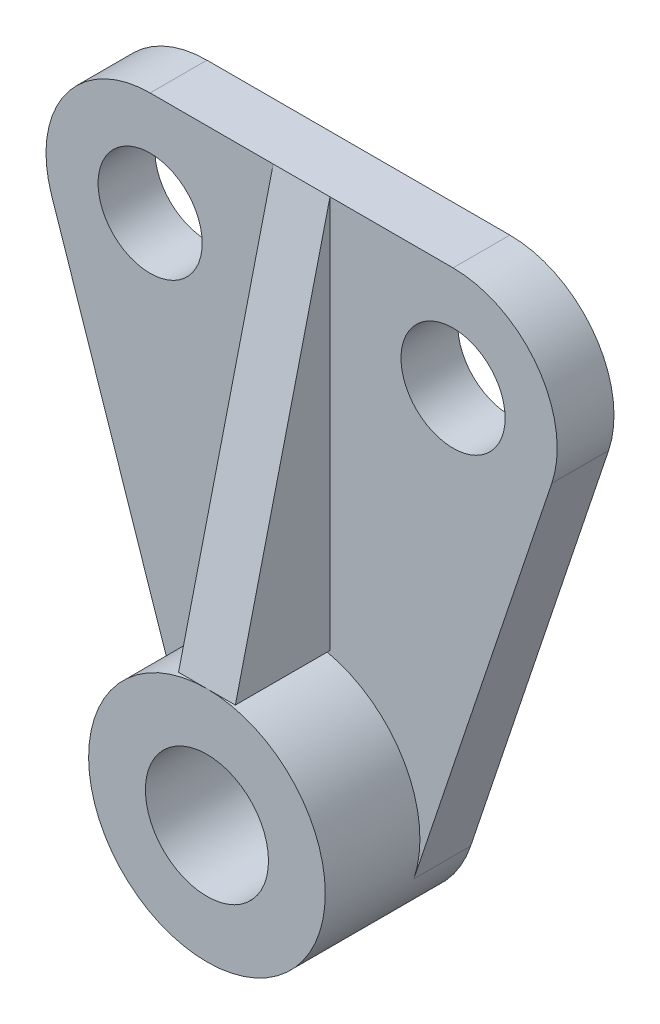
SolidWorks part; units mm, degrees
ref_plane "Ön Düzlem" through (0, 0, 0) normal (0, 0, 1) x (1, 0, 0)
ref_plane "Üst Düzlem" through (0, 0, 0) normal (0, 1, 0) x (1, 0, 0)
ref_plane "Sağ Düzlem" through (0, 0, 0) normal (1, 0, 0) x (0, 0, -1)
sketch "Çizim1" plane through (0, 0, 0) normal (0, 0, 1) x (1, 0, 0)
  line L0 (-74.0259, 60.3022) -> (-10.0259, 60.3022)
  line L1 (-94.8846, 31.3083) -> (-65.729, -55.6455)
  line L2 (10.8328, 31.3083) -> (-18.3228, -55.6455)
  arc A0 (-74.0259, 60.3022) -> (-94.8846, 31.3083) centre (-74.0259, 38.3022) ccw
  arc A1 (10.8328, 31.3083) -> (-10.0259, 60.3022) centre (-10.0259, 38.3022) ccw
  arc A2 (-65.729, -55.6455) -> (-18.3228, -55.6455) centre (-42.0259, -47.6978) ccw
  circle A3 centre (-74.0259, 38.3022) radius 11
  circle A4 centre (-10.0259, 38.3022) radius 11
  circle A5 centre (-42.0259, -47.6978) radius 13
  dimension "D1" = 44
  dimension "D2" = 44
  dimension "D3" = 50
  dimension "D6" = 22
  dimension "D7" = 22
  dimension "D8" = 26
  dimension "D4" = 64
  dimension "D5" = 108
  dimension "D9" = 32
extrude "Yükseklik-Ekstrüzyon9" add sketch "Çizim1" along normal blind 12
sketch "Çizim11" plane through (0, 0, 12) normal (0, 0, 1) x (1, 0, 0)
  circle A0 centre (-42.0259, -47.6978) radius 25
extrude "Yükseklik-Ekstrüzyon10" add sketch "Çizim11" along normal blind 20
sketch "Çizim12" plane through (0, 0, 32) normal (0, 0, 1) x (1, 0, 0)
  circle A0 centre (-42.0259, -47.6978) radius 13
  dimension "D1" = 26
extrude "Kes-Ekstrüzyon4" cut sketch "Çizim12" against normal up to next
sketch "Çizim13" plane through (0, 0, 12) normal (0, 0, 1) x (1, 0, 0)
  line L0 (-10.0259, 60.3022) -> (-74.0259, 60.3022) construction
  line L1 (-48.0259, 60.3022) -> (-36.0259, 60.3022)
  line L2 (-48.0259, 60.3022) -> (-48.0259, -22.6978)
  line L3 (-48.0259, -22.6978) -> (-36.0259, -22.6978)
  line L4 (-36.0259, 60.3022) -> (-36.0259, -22.6978)
  circle A0 centre (-74.0259, 38.3022) radius 11 construction
  dimension "D2" = 26
  dimension "D1" = 12
extrude "Yükseklik-Ekstrüzyon32" add sketch "Çizim13" along normal blind 20 and the other way blind 1 separate body contours L2 L1 L4 L3
sketch "Çizim14" plane through (-48.0259, 0, 0) normal (-1, 0, 0) x (0, 0, 1)
  line L0 (12, 60.3022) -> (32, -22.6978)
  line L1 (32, -22.6978) -> (32, 60.3022)
  line L2 (32, 60.3022) -> (12, 60.3022)
extrude "Kes-Ekstrüzyon5" cut sketch "Çizim14" against normal up to next (12 mm away) contours L2 L0 L1
